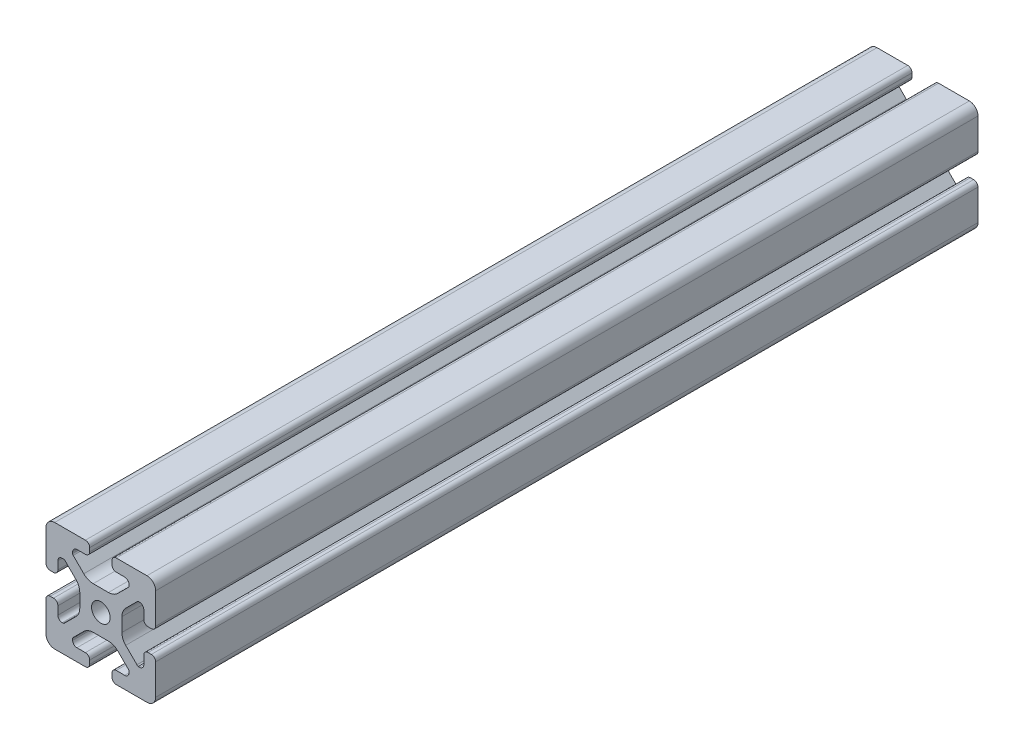
SolidWorks part; units mm, degrees
material "6061 Alloy"
ref_plane "Front Plane" through (0, 0, 0) normal (0, 0, 1) x (1, 0, 0)
ref_plane "Top Plane" through (0, 0, 0) normal (0, 1, 0) x (1, 0, 0)
ref_plane "Right Plane" through (0, 0, 0) normal (1, 0, 0) x (0, 0, -1)
sketch "Sketch1" plane through (0, 0, 0) normal (0, 0, 1) x (1, 0, 0)
  line L0 (0, 19.7407) -> (0, -19.7407) construction
  line L1 (19.0335, 0) -> (-20.7246, 0) construction
  line L2 (-8.715, -15.5246) -> (-5.63, -15.5246)
  line L3 (-10.285, -13.9546) -> (-10.285, -13.4925)
  line L4 (-6.2171, -9.1098) -> (-10.0624, -12.9551)
  line L5 (2.7773, -7.685) -> (-2.7773, -7.685)
  line L6 (10.0624, -12.9551) -> (6.2171, -9.1098)
  line L7 (10.285, -13.9546) -> (10.285, -13.4925)
  line L8 (5.63, -15.5246) -> (8.715, -15.5246)
  line L9 (4.06, -18.43) -> (4.06, -17.0946)
  line L10 (-4.06, -18.43) -> (-4.06, -17.0946)
  line L11 (15.68, -8.7154) -> (15.68, -5.63)
  line L12 (-14.11, -10.2854) -> (-13.8169, -10.2854)
  line L13 (20, -16.83) -> (20, -5.63)
  line L14 (20, 5.63) -> (20, 13.0011)
  line L15 (-16.83, 20) -> (-5.63, 20)
  line L16 (5.63, 20) -> (12.9796, 20)
  line L18 (-8.715, 15.5246) -> (-5.63, 15.5246)
  line L19 (-20, -17.0184) -> (-20, -5.7579)
  line L20 (-20, 5.573) -> (-20, 13.0045)
  line L21 (-15.68, -8.7154) -> (-15.68, -5.7579)
  line L23 (-16.6746, -20) -> (-5.63, -20)
  line L24 (5.63, -20) -> (13, -20)
  line L53 (14.11, -10.2854) -> (13.6201, -10.2854)
  line L54 (13.1637, -9.947) -> (9.0762, -5.8595)
  line L55 (7.685, -2.5008) -> (7.685, 2.5008)
  line L56 (9.0762, 5.8595) -> (13.2795, 10.0628)
  line L57 (13.8169, 10.2854) -> (14.11, 10.2854)
  line L58 (15.68, 8.7154) -> (15.68, 5.63)
  line L59 (17.25, 4.06) -> (18.43, 4.06)
  line L61 (20, 13.0011) -> (20, 16.83)
  line L62 (16.83, 20) -> (12.9796, 20)
  line L64 (4.06, 18.43) -> (4.06, 17.0946)
  line L65 (5.63, 15.5246) -> (8.715, 15.5246)
  line L66 (10.285, 13.9546) -> (10.285, 13.4925)
  line L67 (10.0624, 12.9551) -> (6.2171, 9.1098)
  line L68 (2.7773, 7.685) -> (-2.7773, 7.685)
  line L69 (-6.2171, 9.1098) -> (-10.0624, 12.9551)
  line L70 (-10.285, 13.4925) -> (-10.285, 13.9546)
  line L72 (-4.06, 17.0946) -> (-4.06, 18.43)
  line L75 (-20, 16.83) -> (-20, 13.0045)
  line L77 (-18.43, 4.003) -> (-17.25, 4.003)
  line L78 (-15.68, 5.573) -> (-15.68, 8.4757)
  line L79 (-14.0552, 10.0447) -> (-13.7199, 10.033)
  line L80 (-13.0405, 9.8238) -> (-9.0762, 5.8595)
  line L81 (-7.685, 2.5008) -> (-7.685, -2.5008)
  line L82 (-9.0762, -5.8595) -> (-13.2795, -10.0628)
  line L85 (-17.25, -4.1204) -> (-18.43, -4.1204)
  line L100 (13, -20) -> (16.83, -20)
  line L103 (18.43, -4.06) -> (17.25, -4.06)
  arc A0 (-5.63, -15.5246) -> (-4.06, -17.0946) centre (-5.63, -17.0946) cw
  arc A1 (-8.715, -15.5246) -> (-10.285, -13.9546) centre (-8.715, -13.9546) cw
  arc A2 (-10.285, -13.4925) -> (-10.0624, -12.9551) centre (-9.525, -13.4925) cw
  arc A3 (-6.2171, -9.1098) -> (-2.7773, -7.685) centre (-2.7773, -12.5496) cw
  arc A4 (2.7773, -7.685) -> (6.2171, -9.1098) centre (2.7773, -12.5496) cw
  arc A5 (10.0624, -12.9551) -> (10.285, -13.4925) centre (9.525, -13.4925) cw
  arc A6 (10.285, -13.9546) -> (8.715, -15.5246) centre (8.715, -13.9546) cw
  arc A7 (4.06, -17.0946) -> (5.63, -15.5246) centre (5.63, -17.0946) cw
  arc A8 (5.63, -20) -> (4.06, -18.43) centre (5.63, -18.43) cw
  arc A9 (-4.06, -18.43) -> (-5.63, -20) centre (-5.63, -18.43) cw
  circle A45 centre (0, 0) radius 3.4
  arc A46 (17.25, -4.06) -> (15.68, -5.63) centre (17.25, -5.63) ccw
  arc A47 (14.11, -10.2854) -> (15.68, -8.7154) centre (14.11, -8.7154) ccw
  arc A48 (13.1637, -9.947) -> (13.6201, -10.2854) centre (13.8117, -9.55) ccw
  arc A49 (7.685, -2.5008) -> (9.0762, -5.8595) centre (12.435, -2.5008) ccw
  arc A50 (9.0762, 5.8595) -> (7.685, 2.5008) centre (12.435, 2.5008) ccw
  arc A51 (13.8169, 10.2854) -> (13.2795, 10.0628) centre (13.8169, 9.5254) ccw
  arc A52 (15.68, 8.7154) -> (14.11, 10.2854) centre (14.11, 8.7154) ccw
  arc A53 (15.68, 5.63) -> (17.25, 4.06) centre (17.25, 5.63) ccw
  arc A54 (18.43, 4.06) -> (20, 5.63) centre (18.43, 5.63) ccw
  arc A55 (20, 16.83) -> (16.83, 20) centre (16.83, 16.83) ccw
  arc A56 (5.63, 20) -> (4.06, 18.43) centre (5.63, 18.43) ccw
  arc A57 (4.06, 17.0946) -> (5.63, 15.5246) centre (5.63, 17.0946) ccw
  arc A58 (10.285, 13.9546) -> (8.715, 15.5246) centre (8.715, 13.9546) ccw
  arc A59 (10.0624, 12.9551) -> (10.285, 13.4925) centre (9.525, 13.4925) ccw
  arc A60 (2.7773, 7.685) -> (6.2171, 9.1098) centre (2.7773, 12.5496) ccw
  arc A61 (-6.2171, 9.1098) -> (-2.7773, 7.685) centre (-2.7773, 12.5496) ccw
  arc A62 (-10.285, 13.4925) -> (-10.0624, 12.9551) centre (-9.525, 13.4925) ccw
  arc A63 (-8.715, 15.5246) -> (-10.285, 13.9546) centre (-8.715, 13.9546) ccw
  arc A64 (-5.63, 15.5246) -> (-4.06, 17.0946) centre (-5.63, 17.0946) ccw
  arc A65 (-4.06, 18.43) -> (-5.63, 20) centre (-5.63, 18.43) ccw
  arc A66 (-16.83, 20) -> (-20, 16.83) centre (-16.83, 16.83) ccw
  arc A67 (-20, 5.573) -> (-18.43, 4.003) centre (-18.43, 5.573) ccw
  arc A68 (-17.25, 4.003) -> (-15.68, 5.573) centre (-17.25, 5.573) ccw
  arc A69 (-14.0552, 10.0447) -> (-15.68, 8.4757) centre (-14.11, 8.4757) ccw
  arc A70 (-13.0405, 9.8238) -> (-13.7199, 10.033) centre (-13.5779, 9.2864) ccw
  arc A71 (-7.685, 2.5008) -> (-9.0762, 5.8595) centre (-12.435, 2.5008) ccw
  arc A72 (-9.0762, -5.8595) -> (-7.685, -2.5008) centre (-12.435, -2.5008) ccw
  arc A73 (-13.8169, -10.2854) -> (-13.2795, -10.0628) centre (-13.8169, -9.5254) ccw
  arc A74 (-15.68, -8.7154) -> (-14.11, -10.2854) centre (-14.11, -8.7154) ccw
  arc A75 (-15.68, -5.7579) -> (-17.25, -4.1204) centre (-17.2485, -5.6904) ccw
  arc A76 (-18.43, -4.1204) -> (-20, -5.7579) centre (-18.4315, -5.6904) ccw
  arc A77 (-20, -17.0184) -> (-16.6746, -20) centre (-16.8354, -16.8341) ccw
  arc A88 (16.83, -20) -> (20, -16.83) centre (16.83, -16.83) ccw
  arc A89 (20, -5.63) -> (18.43, -4.06) centre (18.43, -5.63) ccw
  dimension "D2" = 6.8
  dimension "D7" = 20.57
  dimension "D1" = 40
  dimension "D3" = 4.32
  dimension "D4" = 15.37
  dimension "D5" = 20
  dimension "D6" = 4.32
  dimension "D9" = 15.37
extrude "Extrude1" add sketch "Sketch1" against normal blind 300
equation "\"PinDiameter\"= 0"
equation "\"WallThickness\"= 0.5cm"
equation "\"BottomPlateX\"= 100cm"
equation "\"BottomPlateZ\"= 70cm"
equation "\"BottomPlateHoleD\"=((\"ArmPlateX\")^2+(\"ArmPlateDepth\")^2)^.5+ 10mm"
equation "\"ActuatorL\"= 35cm"
equation "\"ActuatorPinD\"= 6.35mm"
equation "\"ActuatorPinL\"= 15cm"
equation "\"Box-X\"= 40cm"
equation "\"Box-Z\"= 20cm"
equation "\"Box-Y\"= 30cm"
equation "\"ArmPlateThickness\"= 1cm"
equation "\"ArmPlateX\"= 50cm"
equation "\"ArmPlateDepth\"= 20cm"
equation "\"Arm1X\"= 5cm"
equation "\"Arm1L\"= 60cm"
equation "\"Arm2GAP\"= 5cm"
equation "\"Arm2L\"= 60cm"
equation "\"Arm2H\"= 5cm"
equation "\"Arm2Extension\"= 5cm"
equation "\"Arm3GAP\"= 5cm"
equation "\"Arm3L\"= 60cm"
equation "\"Arm3H\"= 5cm"
equation "\"Pin1-2L\"= \"Arm2GAP\" + (2 * \"WallThickness\")"
equation "\"Pin2-3L\"= \"Arm3GAP\" + (4 * \"WallThickness\")"
equation "\"DCMotor1D\"= 65mm"
equation "\"DCMotor1L\"= 215mm"
equation "\"DCMotor1ShaftL\"= 30mm"
equation "\"DCMotor2X\"= 68mm"
equation "\"DCMotor2D\"= 65mm"
equation "\"DCMotor2L\"= 215mm"
equation "\"DCMotor2ShaftL\"= 30mm"
equation "\"DCMotor2ShaftD\"= 15mm"
equation "\"BenchDepth\"= 5cm"
equation "\"BenchH\"= 10cm"
equation "\"BenchL\"= 15cm"
equation "\"PillowBlockW\"= 5cm"
equation "\"PillowBlockCenterH\"= \"DCMotor2X\"/2"
equation "\"EncoderRadius\"= 19mm"
equation "\"EncoderShaftL\"= 15mm"
equation "\"EncoderL\"= 33mm"
equation "\"EncoderHousingThickness\"= 7.5mm"
equation "\"TurntableID\"= 70mm"
equation "\"TurntableInner2*t\" = (\"TurntableOD\"-\"TurntableID\")*.25 - .5mm"
equation "\"TurntableInnerHoleRadius\"= \"TurntableID\"*.5 + \"TurntableInner2*t\"*.5"
equation "\"TurntableOD\"= 120mm"
equation "\"TurntableOuterHoleRadius\" = \"TurntableOD\"*.5 - ((\"TurntableOD\"-\"TurntableID\")*.25-.5mm)*.5"
equation "\"4040Height\" = 30cm"
equation "\"LENGTH@Extrude1\"=\"4040Height\""
